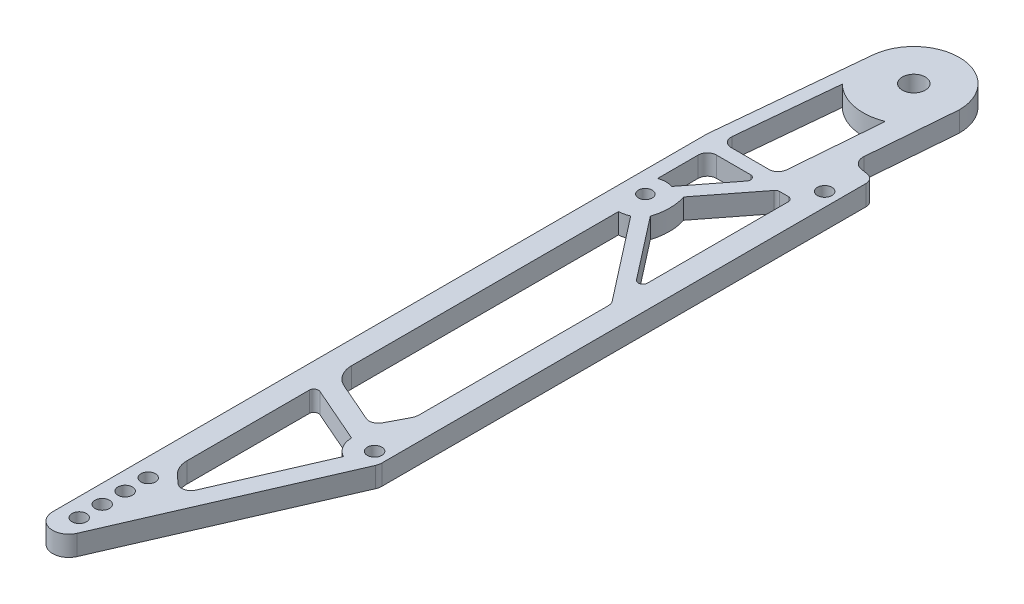
SolidWorks part; units mm, degrees
material "6061-T6 (SS)"
ref_plane "X-Y Datum" through (0, 0, 0) normal (0, 0, 1) x (1, 0, 0)
ref_plane "X-Z Datum" through (0, 0, 0) normal (0, 1, 0) x (1, 0, 0)
ref_plane "Y-Z Datum" through (0, 0, 0) normal (1, 0, 0) x (0, 0, -1)
other "Graphic1" [suppressed]
other "Graphic (Closed) -1" [suppressed]
sketch "Sketch2" plane through (0, 0, 0) normal (0, 1, 0) x (1, 0, 0)
  line L5 (13.4859, -162.4108) -> (-10.16, -152.0908) construction
  line L8 (0, 0) -> (0, -24.13) construction
  line L11 (15.1556, -28.0184) -> (13.2387, -27.713)
  line L15 (-16.51, -221.3289) -> (-16.51, -40.7097)
  line L22 (-7.9887, -223.1013) -> (16.9799, -165.6775)
  line L23 (17.2959, -164.1583) -> (17.2959, -30.5268)
  line L33 (10.4385, -167.9818) -> (-1.9175, -196.3988)
  line L39 (10.9459, -147.5171) -> (10.9459, -95.2658)
  line L40 (10.4113, -93.707) -> (-7.4332, -70.7494)
  line L42 (-10.16, -71.4177) -> (-10.16, -145.1624)
  line L44 (-4.6584, -58.8889) -> (6.2711, -44.8278)
  line L45 (7.2738, -44.3372) -> (9.6759, -44.3372)
  line L46 (10.9459, -45.6072) -> (10.9459, -84.4832)
  line L47 (8.6732, -85.2626) -> (-4.6584, -68.1111)
  line L49 (-12.4152, -37.7444) -> (-9.7512, -10.0037)
  line L51 (5.1277, -12.9949) -> (3.0693, -38.194)
  line L53 (0.5377, -40.5272) -> (-9.8869, -40.5272)
  line L56 (-0.7688, -44.3372) -> (-10.1425, -44.3372)
  line L57 (13.7382, -24.5776) -> (0, 0) construction
  line L58 (10.5738, -24.3191) -> (12.5603, 0)
  line L59 (-10.16, -156.8022) -> (-10.16, -190.5798)
  line L60 (-8.1454, -195.2196) -> (-5.981, -197.2419)
  line L62 (4.4882, -155.7125) -> (-6.35, -150.9823)
  line L63 (7.1359, -162.4108) -> (-8.382, -155.6382)
  line L64 (-12.6825, -58.0933) -> (-12.6825, -46.8772)
  line L65 (0.2339, -46.3866) -> (-8.8141, -58.0272)
  line L66 (-16.4926, -40.3455) -> (-12.5028, 1.2007)
  line L67 (0.647, -159.5788) -> (2.679, -154.9229) construction
  line L68 (4.2397, -44.3372) -> (-10.6553, -63.5) construction
  line L69 (-1.7037, -55.0877) -> (-4.7119, -52.7495) construction
  line L70 (9.4418, -89.3556) -> (-10.6553, -63.5) construction
  line L71 (10.9459, -88.1865) -> (7.9378, -90.5247) construction
  line L75 (10.513, -149.281) -> (7.7556, -154.5604)
  circle A0 centre (0, 0) radius 3.175
  circle A2 centre (-11.43, -219.075) radius 2
  circle A3 centre (-11.43, -212.725) radius 2
  circle A4 centre (-11.43, -206.375) radius 2
  circle A5 centre (-11.43, -200.025) radius 2
  circle A7 centre (0, 0) radius 12.5603 construction
  circle A8 centre (-10.6553, -63.5) radius 1.905
  circle A12 centre (13.4859, -38.1) radius 2
  arc A13 (-12.5028, 1.2007) -> (12.5603, 0) centre (0, 0) cw
  arc A14 (-4.6584, -68.1111) -> (-4.6584, -58.8889) centre (-18.9173, -63.5) ccw
  circle A16 centre (24.0125, -14.7036) radius 3.175 construction
  arc A17 (24.0125, -14.7036) -> (13.7382, -24.5776) centre (0, 0) cw construction
  circle A18 centre (13.7382, -24.5776) radius 3.175 construction
  arc A19 (13.2387, -27.713) -> (10.5738, -24.3191) centre (13.7382, -24.5776) cw
  arc A20 (15.1556, -28.0184) -> (17.2959, -30.5268) centre (14.7559, -30.5268) cw
  circle A21 centre (13.4859, -162.4108) radius 2
  arc A24 (10.4385, -167.9818) -> (7.1359, -162.4108) centre (13.4859, -162.4108) cw
  arc A25 (-16.51, -221.3289) -> (-7.9887, -223.1013) centre (-12.065, -221.3289) ccw
  arc A26 (-12.6825, -58.0933) -> (-8.8141, -58.0272) centre (-10.6553, -63.5) cw
  arc A27 (-7.4332, -70.7494) -> (-10.16, -71.4177) centre (-10.6553, -63.5) cw
  arc A28 (5.1277, -12.9949) -> (-9.7512, -10.0037) centre (0, 0) cw
  arc A29 (-10.16, -190.5798) -> (-8.1454, -195.2196) centre (-3.81, -190.5798) ccw
  arc A30 (-5.981, -197.2419) -> (-1.9175, -196.3988) centre (-4.2469, -195.386) ccw
  arc A31 (-10.1425, -44.3372) -> (-12.6825, -46.8772) centre (-10.1425, -46.8772) ccw
  arc A32 (-12.4152, -37.7444) -> (-9.8869, -40.5272) centre (-9.8869, -37.9872) ccw
  arc A33 (0.5377, -40.5272) -> (3.0693, -38.194) centre (0.5377, -37.9872) ccw
  arc A34 (10.4113, -93.707) -> (10.9459, -95.2658) centre (8.4059, -95.2658) cw
  arc A35 (-10.16, -145.1624) -> (-6.35, -150.9823) centre (-3.81, -145.1624) ccw
  arc A36 (-10.16, -156.8022) -> (-8.382, -155.6382) centre (-8.89, -156.8022) cw
  arc A37 (8.6732, -85.2626) -> (10.9459, -84.4832) centre (9.6759, -84.4832) ccw
  arc A38 (6.2711, -44.8278) -> (7.2738, -44.3372) centre (7.2738, -45.6072) cw
  arc A39 (9.6759, -44.3372) -> (10.9459, -45.6072) centre (9.6759, -45.6072) cw
  arc A40 (-0.7688, -44.3372) -> (0.2339, -46.3866) centre (-0.7688, -45.6072) cw
  arc A48 (4.4882, -155.7125) -> (7.7556, -154.5604) centre (5.5042, -153.3845) ccw
  arc A49 (-16.4926, -40.3455) -> (-16.51, -40.7097) centre (-12.7, -40.7097) ccw
  arc A50 (17.2959, -164.1583) -> (16.9799, -165.6775) centre (13.4859, -164.1583) cw
  arc A51 (10.9459, -147.5171) -> (10.513, -149.281) centre (7.1359, -147.5171) cw
  point P30 (17.2959, -28.3595)
  point P37 (1.663, -157.2508)
  point P44 (-3.2078, -53.9186)
  point P65 (9.4418, -89.3556)
  point P88 (-12.6825, -44.3372)
  point P91 (-12.6825, -40.5272)
  point P96 (10.9459, -94.3948)
  point P99 (-10.16, -149.3195)
  point P104 (10.9459, -88.1865)
  point P107 (6.6524, -44.3372)
  point P110 (10.9459, -44.3372)
  point P117 (-16.51, -40.5272)
  point P120 (17.2959, -164.9508)
  dimension "D1" = 6.35
  dimension "D6" = 4
  dimension "D12" = 24.13
  dimension "D5" = 25.1206
  dimension "D14" = 3.81
  dimension "D19" = 4
  dimension "D20" = 6.35
  dimension "D24" = 3.81
  dimension "D50" = 14.986
  dimension "D51" = 8.262
  dimension "D42" = 4.826
  dimension "D62" = 6.35
  dimension "D63" = 29.204
  dimension "D27" = 2.54
  dimension "D44" = 4
  dimension "D18" = 4.445
  dimension "D34" = 3.81
  dimension "D36" = 6.35
  dimension "D33" = 13.97
  dimension "D38" = 2.54
  dimension "D39" = 6.35
  dimension "D48" = 2.54
  dimension "D49" = 1.27
  dimension "D52" = 6.35
  dimension "D53" = 3.81
  dimension "D54" = 2.54
  dimension "D58" = 3.81
  dimension "D7" = 6.35
  dimension "D8" = 6.35
  dimension "D9" = 6.35
  dimension "D10" = 5.08
  dimension "D11" = 5.08
  dimension "D13" = 4.1084
  dimension "D15" = 63.5
  dimension "D16" = 10.6553
  dimension "D17" = 13.7382
  dimension "D21" = 136.5913
  dimension "D22" = 38.1
  dimension "D23" = 13.4859
  dimension "D25" = 6.35
  dimension "D26" = 3.81
  dimension "D28" = 40.5272
  dimension "D29" = 6.35
  dimension "D30" = 2.54
  dimension "D31" = 5.08
  dimension "D32" = 3.81
  dimension "D35" = 3.81
  dimension "D37" = 16.51
  dimension "D40" = 23.5
  dimension "D41" = 7.62
  dimension "D43" = 200.025
  dimension "D45" = 6.35
  dimension "D46" = 6.35
  dimension "D47" = 4.2935
  dimension "D55" = 94
  dimension "D56" = 3.81
  dimension "D57" = 9.398
  dimension "D60" = 24.0125
  dimension "D61" = 14.7036
extrude "Boss-Extrude1" add sketch "Sketch2" along normal blind 5.588
sketch "Sketch4" plane through (0, 5.588, 0) normal (0, 1, 0) x (1, 0, 0)
  line L0 (0, 0) -> (0, -29.0331) construction
sketch "Sketch6" plane through (-16.51, 0, 0) normal (-1, 0, 0) x (0, 0, 1)
  line L0 (183.2289, 5.588) -> (183.2289, 0)
  line L1 (40.7097, 5.588) -> (221.3289, 5.588) construction
  line L2 (40.7097, 0) -> (221.3289, 0) construction
  line L3 (221.3289, 5.588) -> (221.3289, 0) construction
  dimension "D1" = 38.1
split line "Split Line2"
